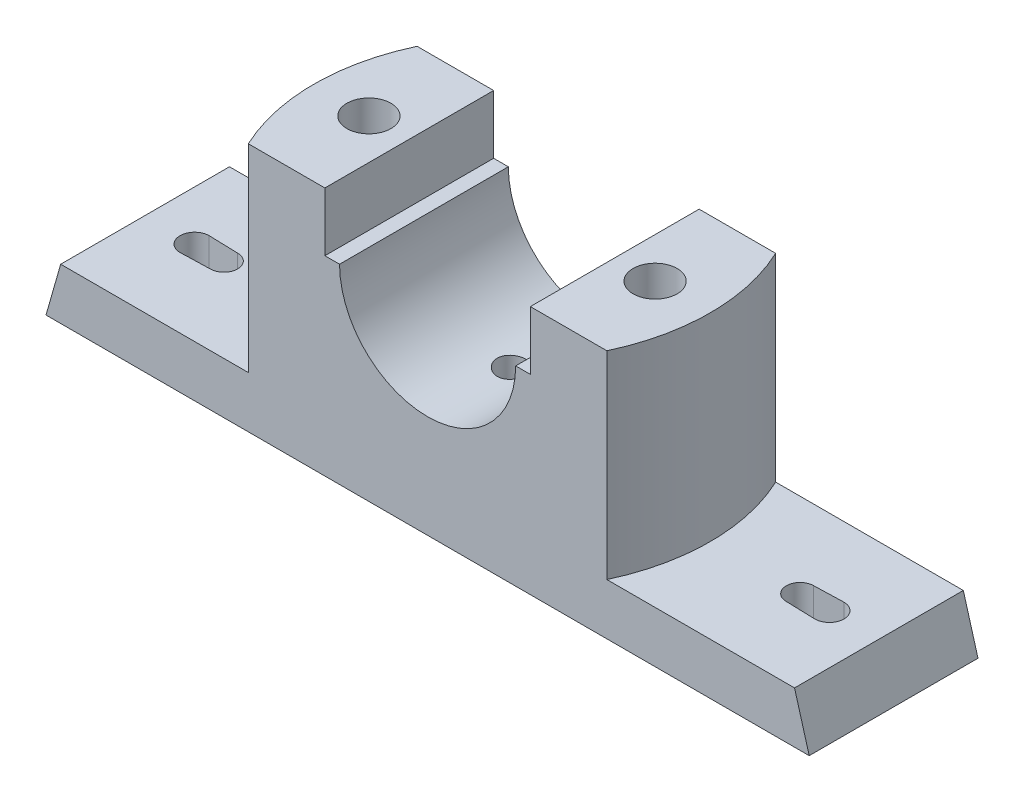
SolidWorks part; units mm, degrees
ref_plane "Front Plane" through (0, 0, 0) normal (0, 0, 1) x (1, 0, 0)
ref_plane "Top Plane" through (0, 0, 0) normal (0, 1, 0) x (1, 0, 0)
ref_plane "Right Plane" through (0, 0, 0) normal (1, 0, 0) x (0, 0, -1)
sketch "Sketch1" plane through (0, 0, 0) normal (0, 0, 1) x (1, 0, 0)
  line L0 (-75.4118, 0) -> (80.3529, 0) construction
  line L1 (0, 44.1176) -> (0, -51.8824) construction
  line L2 (100, 4.4706) -> (104, -9.5294)
  line L3 (-100, 4.4706) -> (-54, 4.4706)
  line L4 (-54, 4.4706) -> (-54, 58.4706)
  line L5 (-54, 58.4706) -> (-28, 58.4706)
  line L6 (-28, 58.4706) -> (-28, 42.4706)
  line L7 (-28, 42.4706) -> (-24, 42.4706)
  line L8 (-104, -9.5294) -> (104, -9.5294)
  line L9 (28, 42.4706) -> (24, 42.4706)
  line L11 (28, 58.4706) -> (28, 42.4706)
  line L12 (54, 58.4706) -> (28, 58.4706)
  line L13 (54, 4.4706) -> (54, 58.4706)
  line L14 (100, 4.4706) -> (54, 4.4706)
  line L16 (-100, 4.4706) -> (-104, -9.5294)
  arc A0 (-24, 42.4706) -> (24, 42.4706) centre (0, 42.4706) ccw
  point P18 (0, -9.5294)
  dimension "D7" = 53.6471
  dimension "D9" = 24
  dimension "D1" = 16
  dimension "D2" = 54
  dimension "D3" = 14
  dimension "D4" = 28
  dimension "D5" = 54
  dimension "D6" = 104
extrude "Boss-Extrude1" add sketch "Sketch1" along normal mid plane 46
sketch "Sketch2" plane through (0, 58.4706, 0) normal (0, 1, 0) x (1, 0, 0)
  circle A0 centre (-39, 0) radius 6
  circle A1 centre (39, 0) radius 6
  dimension "D1" = 12
  dimension "D2" = 12
  dimension "D3" = 78
  dimension "D4" = 39
extrude "Cut-Extrude1" cut sketch "Sketch2" against normal through all
sketch "Sketch3" plane through (0, 58.4706, 0) normal (0, 1, 0) x (1, 0, 0)
  line L0 (-48.8569, 23) -> (-69.8016, 23)
  line L1 (-28, 23) -> (-54, 23) construction
  line L2 (-54, 23) -> (-100, 23) construction
  line L3 (-69.8016, 23) -> (-69.8016, -23)
  line L4 (-54, -23) -> (-100, -23) construction
  line L5 (-69.8016, -23) -> (-48.8569, -23)
  line L6 (-28, -23) -> (-54, -23) construction
  line L7 (0, 63.907) -> (0, -45.4424) construction
  line L8 (69.8016, -23) -> (48.8569, -23)
  line L9 (48.8569, 23) -> (69.8016, 23)
  line L10 (69.8016, 23) -> (69.8016, -23)
  arc A0 (-48.8569, 23) -> (-48.8569, -23) centre (0, 0) ccw
  arc A1 (48.8569, -23) -> (48.8569, 23) centre (0, 0) ccw
  dimension "D1" = 108
extrude "Cut-Extrude2" cut sketch "Sketch3" against normal up to surface (54 mm away) up to face at (-77, 4.4706, 0)
sketch "Sketch4" plane through (0, 4.4706, 0) normal (0, 1, 0) x (1, 0, 0)
  line L0 (-104, -23) -> (-104, 23) construction
  line L1 (-86.5, 3.9749) -> (-78.5, 3.7322)
  line L2 (-86.5, -3.9749) -> (-78.5, -3.7322)
  arc A0 (-86.259, 3.9676) -> (-86.259, -3.9676) centre (-86.5, 0) ccw
  arc A1 (-78.5, -3.7322) -> (-78.5, 3.7322) centre (-78.5, 0) ccw
  dimension "D1" = 17.5
  dimension "D2" = 8
extrude "Cut-Extrude3" cut sketch "Sketch4" against normal through all contours L2 A1 L1 A0
mirror "Mirror1" about plane through (0, 0, 0) normal (1, 0, 0) of "Cut-Extrude3"
ref_plane "Plane1" through (0, 28.4706, 0) normal (0, 1, 0) x (1, 0, 0)
sketch "Sketch5" plane through (0, 28.4706, 0) normal (0, 1, 0) x (1, 0, 0)
  circle A0 centre (0, 0) radius 4
  dimension "D1" = 8
extrude "Cut-Extrude18" cut sketch "Sketch5" against normal blind 24 contours A0
sketch "Sketch6" plane through (0, -9.5294, 0) normal (0, -1, 0) x (1, 0, 0)
  line L0 (0, 57.6807) -> (0, -69.5521) construction
  line L1 (-52, 13) -> (-26, 13)
  line L2 (-52, 13) -> (-52, -13)
  line L3 (-52, -13) -> (-26, -13)
  line L4 (-26, 13) -> (-26, -13)
  line L5 (-52, 13) -> (-26, -13) construction
  line L6 (-52, -13) -> (-26, 13) construction
  line L7 (52, -13) -> (26, 13) construction
  line L8 (52, 13) -> (26, -13) construction
  line L9 (26, 13) -> (26, -13)
  line L10 (52, -13) -> (26, -13)
  line L11 (52, 13) -> (52, -13)
  line L12 (52, 13) -> (26, 13)
  point P0 (-39, 0)
  point P13 (39, 0)
  dimension "D1" = 26
  dimension "D2" = 26
extrude "Cut-Extrude19" cut sketch "Sketch6" against normal blind 10
